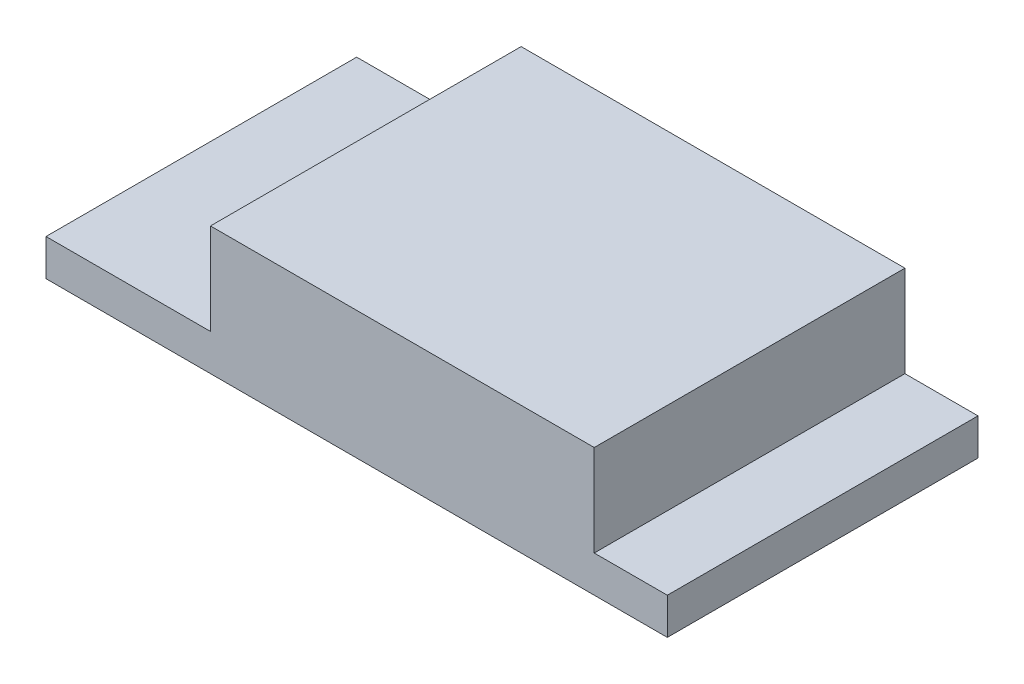
SolidWorks part; units mm, degrees
ref_plane "Front" through (0, 0, 0) normal (0, 0, 1) x (1, 0, 0)
ref_plane "Top" through (0, 0, 0) normal (0, 1, 0) x (1, 0, 0)
ref_plane "Right" through (0, 0, 0) normal (1, 0, 0) x (0, 0, -1)
sketch "Sketch1" plane through (0, 0, 0) normal (0, 1, 0) x (1, 0, 0)
  line L1 (17, -8.5) -> (-17, -8.5)
  line L2 (17, -8.5) -> (17, 8.5)
  line L3 (17, 8.5) -> (-17, 8.5)
  line L4 (-17, -8.5) -> (-17, 8.5)
  line L5 (17, -8.5) -> (-17, 8.5) construction
  line L6 (17, 8.5) -> (-17, -8.5) construction
  point P0 (0, 0)
  dimension "D1" = 34
  dimension "D2" = 17
extrude "Boss-Extrude1" add sketch "Sketch1" along normal blind 2
sketch "Sketch3" plane through (0, 2, 0) normal (0, 1, 0) x (1, 0, 0)
  line L0 (17, 8.5) -> (-17, 8.5) construction
  line L1 (-8, 8.5) -> (13, 8.5)
  line L2 (-8, 8.5) -> (-8, -8.5)
  line L3 (-8, -8.5) -> (13, -8.5)
  line L4 (13, 8.5) -> (13, -8.5)
  line L5 (-17, -8.5) -> (17, -8.5) construction
  line L7 (17, -8.5) -> (17, 8.5) construction
  line L8 (-17, 8.5) -> (-17, -8.5) construction
  dimension "D1" = 4
  dimension "D2" = 21
  dimension "D3" = 9
extrude "Boss-Extrude3" add sketch "Sketch3" along normal blind 5
